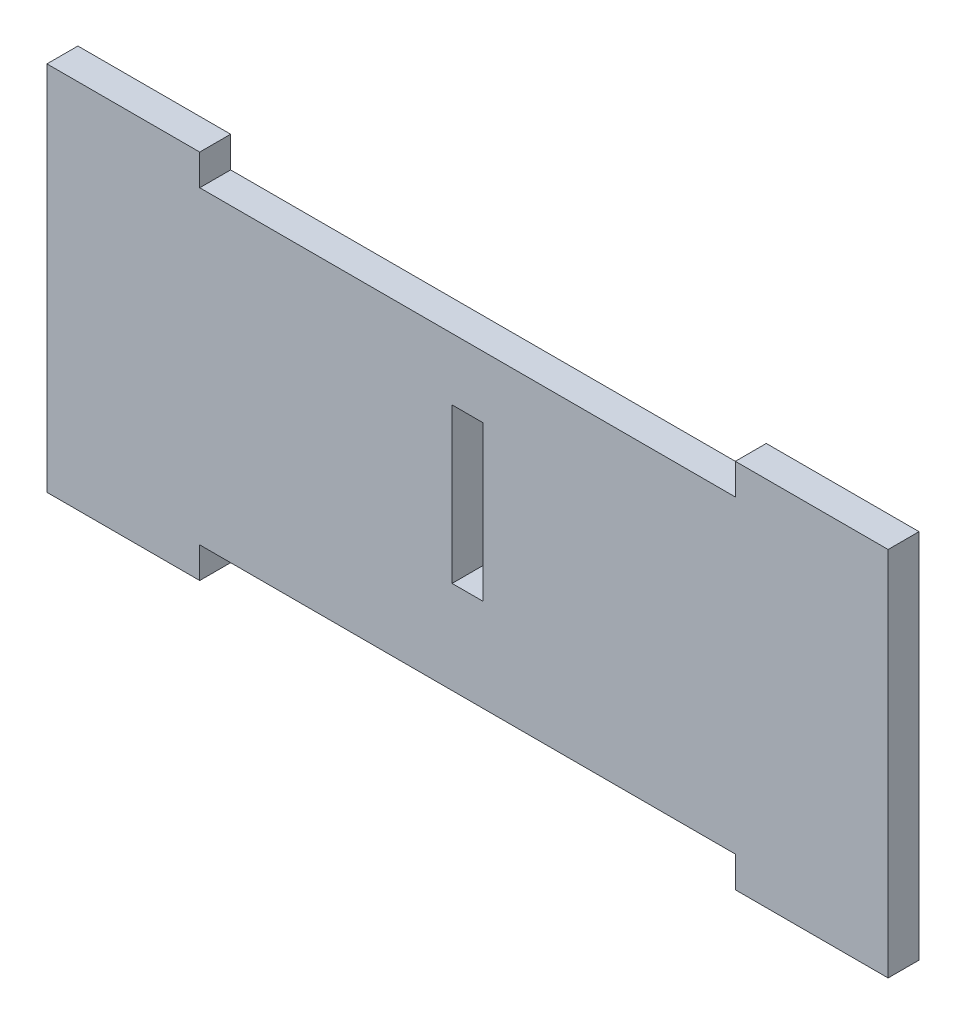
SolidWorks part; units mm, degrees
ref_plane "Front Plane" through (0, 0, 0) normal (0, 0, 1) x (1, 0, 0)
ref_plane "Top Plane" through (0, 0, 0) normal (0, 1, 0) x (1, 0, 0)
ref_plane "Right Plane" through (0, 0, 0) normal (1, 0, 0) x (0, 0, -1)
sketch "Sketch1" plane through (0, 0, 0) normal (0, 0, 1) x (1, 0, 0)
  line L1 (-68, 50) -> (68, 50)
  line L2 (-68, 50) -> (-68, 0)
  line L3 (-68, 0) -> (68, 0)
  line L4 (68, 50) -> (68, 0)
  point P4 (0, 0)
  dimension "D1" = 136
  dimension "D2" = 50
extrude "Boss-Extrude1" add sketch "Sketch1" along normal blind 5
sketch "Sketch2" plane through (0, 50, 0) normal (0, 1, 0) x (1, 0, 0)
  line L0 (68, -5) -> (-68, -5) construction
  line L1 (-68, 0) -> (-43.3, 0)
  line L2 (-68, 0) -> (-68, -5)
  line L3 (-68, -5) -> (-43.3, -5)
  line L4 (-43.3, 0) -> (-43.3, -5)
  line L6 (68, 0) -> (43.3, 0)
  line L7 (68, 0) -> (68, -5)
  line L8 (68, -5) -> (43.3, -5)
  line L9 (43.3, 0) -> (43.3, -5)
  dimension "D1" = 24.7
  dimension "D2" = 24.7
extrude "Boss-Extrude2" add sketch "Sketch2" along normal blind 5
sketch "Sketch3" plane through (0, 0, 0) normal (0, -1, 0) x (1, 0, 0)
  line L0 (-68, 0) -> (68, 0) construction
  line L1 (-68, 5) -> (-43.3, 5)
  line L2 (-68, 5) -> (-68, 0)
  line L3 (-68, 0) -> (-43.3, 0)
  line L4 (-43.3, 5) -> (-43.3, 0)
  line L6 (68, 5) -> (43.3, 5)
  line L7 (68, 5) -> (68, 0)
  line L8 (68, 0) -> (43.3, 0)
  line L9 (43.3, 5) -> (43.3, 0)
  dimension "D1" = 24.7
  dimension "D2" = 24.7
extrude "Boss-Extrude3" add sketch "Sketch3" along normal blind 5
sketch "Sketch4" plane through (0, 0, 5) normal (0, 0, 1) x (1, 0, 0)
  line L0 (-2.5, 15) -> (-2.5, 40)
  line L1 (-2.5, 40) -> (2.5, 40)
  line L2 (2.5, 40) -> (2.5, 15)
  line L3 (2.5, 15) -> (-2.5, 15)
  point P2 (0, 15)
  dimension "D1" = 5
  dimension "D2" = 25
  dimension "D3" = 15
extrude "Cut-Extrude1" cut sketch "Sketch4" against normal up to surface (5 mm away) up to face at (0, 25, 0)
